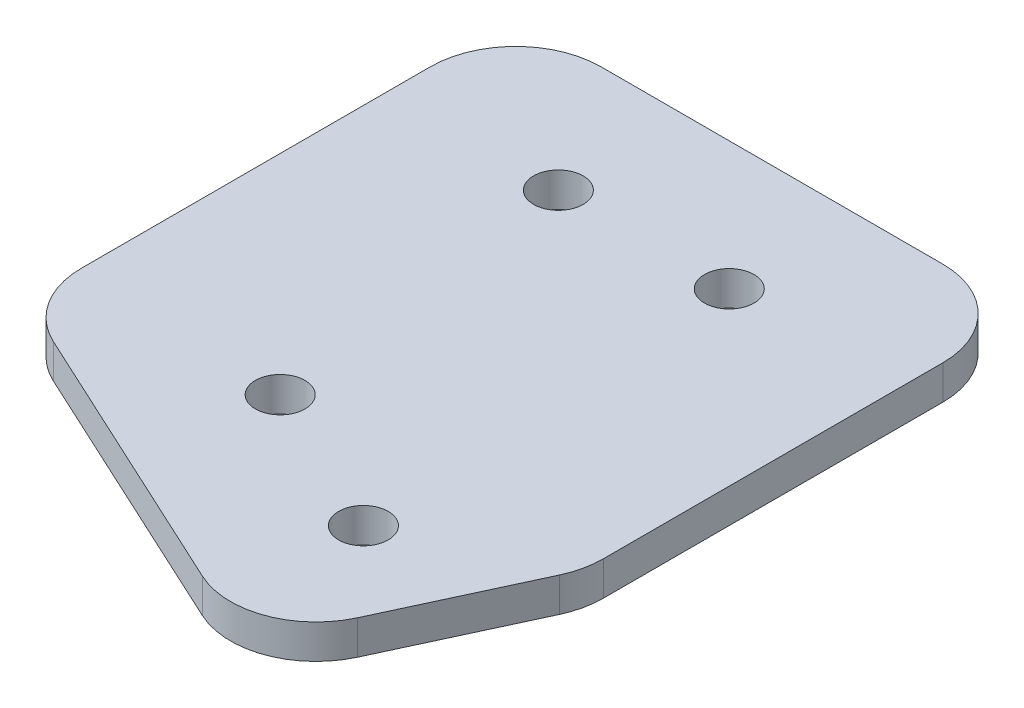
SolidWorks part; units mm, degrees
material "Thornel Mat VMA"
ref_plane "前视基准面" through (0, 0, 0) normal (0, 0, 1) x (1, 0, 0)
ref_plane "上视基准面" through (0, 0, 0) normal (0, 1, 0) x (1, 0, 0)
ref_plane "右视基准面" through (0, 0, 0) normal (1, 0, 0) x (0, 0, -1)
other "Configuration Table"
sketch "草图1" plane through (0, 0, 0) normal (0, 1, 0) x (1, 0, 0)
  line L0 (-223.6957, 111.8771) -> (230, -98.2662) construction
  line L1 (-223.6957, 111.8771) -> (-230, 98.2662) construction
  line L2 (230, -98.2662) -> (223.6957, -111.8771) construction
  line L3 (-230, 98.2662) -> (223.6957, -111.8771) construction
  line L4 (-223.6957, 111.8771) -> (223.6957, -111.8771) construction
  line L5 (230, -98.2662) -> (-230, 98.2662) construction
  line L6 (-230, 98.2662) -> (-230, 57.8051) construction
  line L7 (230, -98.2662) -> (230, 90.5698) construction
  line L8 (-224.5072, 103.9875) -> (265.5077, -122.9782) construction
  line L9 (-230, 126.8771) -> (245, 126.8771) construction
  line L10 (-230, 126.8771) -> (-230, 111.8771) construction
  line L11 (-230, 111.8771) -> (245, 111.8771) construction
  line L12 (245, 126.8771) -> (245, 111.8771) construction
  line L13 (230, 126.8771) -> (245, 126.8771) construction
  line L14 (230, 126.8771) -> (230, -154.4454) construction
  line L15 (230, -154.4454) -> (245, -154.4454) construction
  line L16 (245, 126.8771) -> (245, -154.4454) construction
  line L17 (-245.2365, 119.3771) -> (263.7187, 119.3771) construction
  line L18 (-230, 126.8771) -> (-230, 98.2662)
  line L19 (-230, 98.2662) -> (-206.3043, 87.2908)
  line L20 (-206.3043, 87.2908) -> (-200, 100.9017)
  line L21 (-230, 126.8771) -> (-200, 126.8771)
  line L22 (-200, 126.8771) -> (-200, 100.9017)
  circle A0 centre (-217.7739, 100.8688) radius 1.45
  circle A1 centre (-208.7, 96.6659) radius 1.45
  circle A2 centre (-220, 119.3771) radius 1.45
  circle A3 centre (-210, 119.3771) radius 1.45
  point P1 (0, 0)
  point P31 (0, 0)
  point P32 (-196.8352, 99.4358)
  dimension "D6" = 10
  dimension "D7" = 2.9
  dimension "D10" = 10
  dimension "D12" = 10
  dimension "D1" = 15
  dimension "D2" = 460
  dimension "D3" = 15
  dimension "D4" = 15
  dimension "D5" = 10
  dimension "D8" = 7.5
  dimension "D9" = 10
  dimension "D11" = 500
extrude "凸台-拉伸1" add sketch "草图1" along normal blind 2
fillet "圆角1" radius 5 5 edges at (-200, 1, -100.9017) (-206.3043, 1, -87.2908) (-230, 1, -98.2662) (-200, 1, -126.8771) (-230, 1, -126.8771)
